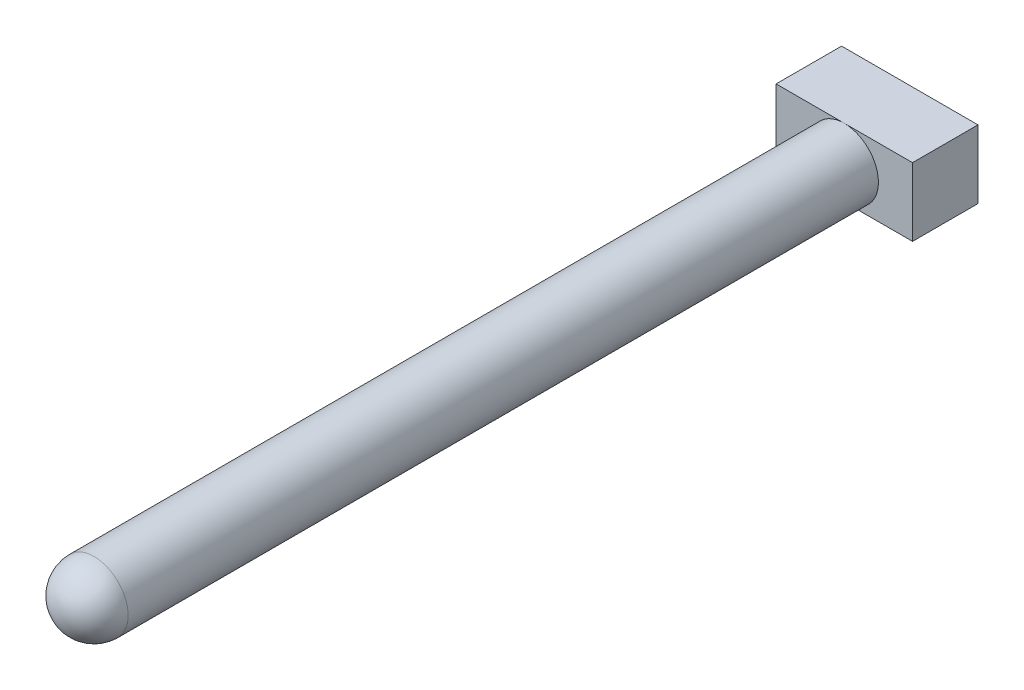
SolidWorks part; units mm, degrees
ref_plane "Front Plane" through (0, 0, 0) normal (0, 0, 1) x (1, 0, 0)
ref_plane "Top Plane" through (0, 0, 0) normal (0, 1, 0) x (1, 0, 0)
ref_plane "Right Plane" through (0, 0, 0) normal (1, 0, 0) x (0, 0, -1)
sketch "Sketch1" plane through (0, 0, 0) normal (0, 0, 1) x (1, 0, 0)
  line L1 (0, 0) -> (12.7, 0)
  line L2 (0, 0) -> (0, 6.35)
  line L3 (0, 6.35) -> (12.7, 6.35)
  line L4 (12.7, 0) -> (12.7, 6.35)
  dimension "D1" = 12.7
  dimension "D2" = 6.35
extrude "Boss-Extrude1" add sketch "Sketch1" along normal blind 6.096
sketch "Sketch2" plane through (0, 0, 6.096) normal (0, 0, 1) x (1, 0, 0)
  line L1 (0, 6.35) -> (12.7, 0) construction
  line L2 (12.7, 6.35) -> (0, 0) construction
  circle A0 centre (6.35, 3.175) radius 3.175
  point P12 (6.35, 3.175)
  point P13 (-4.2652, 4.3465)
  point P14 (-1.9083, 0.6908)
  dimension "D1" = 6.35
extrude "Boss-Extrude2" add sketch "Sketch2" along normal blind 69.85
ref_plane "Plane1" through (6.35, 0, 0) normal (1, 0, 0) x (0, 0, -1)
sketch "Sketch4" plane through (6.35, 0, 0) normal (1, 0, 0) x (0, 0, -1)
  line L0 (-75.946, 6.35) -> (-75.946, 0) construction
  line L1 (-75.946, 6.35) -> (-75.946, 3.175)
  line L2 (-75.946, 3.175) -> (-79.121, 3.175)
  arc A0 (-75.946, 6.35) -> (-79.121, 3.175) centre (-75.946, 3.175) ccw
  dimension "D1" = 6.35
ref_plane "Plane2" through (0, 3.175, 0) normal (0, 1, 0) x (1, 0, 0)
ref_axis "Axis1" through (6.35, 3.175, -3.9561) along (0, 0, 1)
revolve "Revolve1" add sketch "Sketch4" angle 360 about axis through (6.35, 3.175, -3.9561) along (0, 0, 1)
